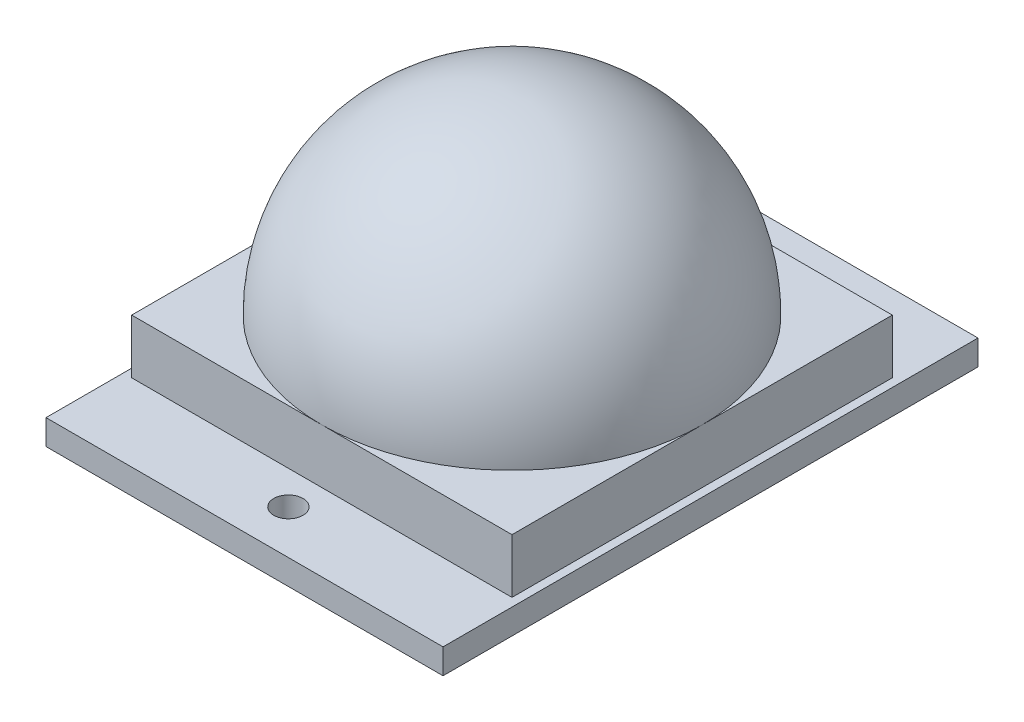
SolidWorks part; units mm, degrees
ref_plane "Front Plane" through (0, 0, 0) normal (0, 0, 1) x (1, 0, 0)
ref_plane "Top Plane" through (0, 0, 0) normal (0, 1, 0) x (1, 0, 0)
ref_plane "Right Plane" through (0, 0, 0) normal (1, 0, 0) x (0, 0, -1)
sketch "Sketch1" plane through (0, 0, 0) normal (0, 1, 0) x (1, 0, 0)
  line L1 (-12.065, -16.256) -> (12.065, -16.256)
  line L2 (-12.065, -16.256) -> (-12.065, 16.256)
  line L3 (-12.065, 16.256) -> (12.065, 16.256)
  line L4 (12.065, -16.256) -> (12.065, 16.256)
  line L5 (-12.065, -16.256) -> (12.065, 16.256) construction
  line L6 (-12.065, 16.256) -> (12.065, -16.256) construction
  point P0 (0, 0)
  dimension "D1" = 32.512
  dimension "D2" = 24.13
extrude "Boss-Extrude1" add sketch "Sketch1" along normal blind 1.524
sketch "Sketch2" plane through (0, 1.524, 0) normal (0, 1, 0) x (1, 0, 0)
  line L1 (11.557, 11.557) -> (-11.557, 11.557)
  line L2 (11.557, 11.557) -> (11.557, -11.557)
  line L3 (11.557, -11.557) -> (-11.557, -11.557)
  line L4 (-11.557, 11.557) -> (-11.557, -11.557)
  line L5 (11.557, 11.557) -> (-11.557, -11.557) construction
  line L6 (11.557, -11.557) -> (-11.557, 11.557) construction
  point P0 (0, 0)
  dimension "D1" = 23.114
  dimension "D2" = 23.114
extrude "Boss-Extrude2" add sketch "Sketch2" along normal blind 3.302
sketch "Sketch4" plane through (0, 0, 0) normal (1, 0, 0) x (0, 0, -1)
  line L0 (-11.557, 4.826) -> (11.557, 4.826) construction
  line L1 (-11.557, 4.826) -> (11.557, 4.826) construction
  line L2 (0, 4.826) -> (0, 16.383)
  line L3 (0, 4.826) -> (-11.557, 4.826)
  arc A0 (0, 16.383) -> (-11.557, 4.826) centre (0, 4.826) ccw
revolve "Revolve1" add sketch "Sketch4" angle 360 about L2
sketch "Sketch5" plane through (0, 1.524, 0) normal (0, 1, 0) x (1, 0, 0)
  line L0 (0, -13.589) -> (0, 13.589) construction
  line L1 (0, 0) -> (-12.065, 0) construction
  line L2 (-12.065, 16.256) -> (-12.065, -16.256) construction
  circle A0 centre (0, -13.589) radius 0.889
  circle A1 centre (0, 13.589) radius 0.889
  dimension "D1" = 1.778
  dimension "D2" = 27.178
extrude "Cut-Extrude1" cut sketch "Sketch5" against normal through all
